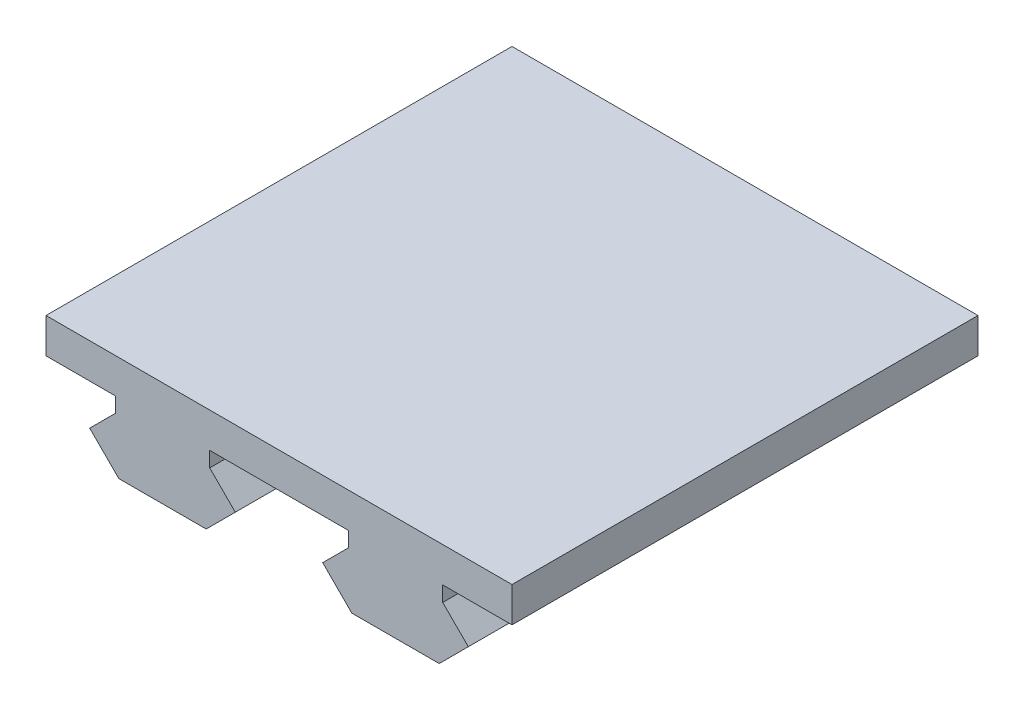
SolidWorks part; units mm, degrees
ref_plane "Front Plane" through (0, 0, 0) normal (0, 0, 1) x (1, 0, 0)
ref_plane "Top Plane" through (0, 0, 0) normal (0, 1, 0) x (1, 0, 0)
ref_plane "Right Plane" through (0, 0, 0) normal (1, 0, 0) x (0, 0, -1)
sketch "Sketch1" plane through (0, 0, 0) normal (0, 1, 0) x (1, 0, 0)
  line L1 (-20, -20) -> (20, -20)
  line L2 (-20, -20) -> (-20, 20)
  line L3 (-20, 20) -> (20, 20)
  line L4 (20, -20) -> (20, 20)
  line L5 (-20, -20) -> (20, 20) construction
  line L6 (-20, 20) -> (20, -20) construction
  point P0 (0, 0)
  dimension "D1" = 40
  dimension "D2" = 40
extrude "Boss-Extrude1" add sketch "Sketch1" along normal blind 3
sketch "Sketch2" plane through (0, 0, 20) normal (0, 0, 1) x (1, 0, 0)
  line L0 (0, 0) -> (-20, 0) construction
  line L1 (-20, 0) -> (20, 0) construction
  line L2 (-10, 0) -> (-10, -6) construction
  line L3 (-13.75, -6) -> (-6.25, -6)
  line L4 (-13.75, -6) -> (-16.25, -3.5)
  line L5 (-16.25, -3.5) -> (-14.0535, -1.3035)
  line L6 (-14.0535, -1.3035) -> (-14.0535, 0)
  line L7 (-14.0535, 0) -> (-5.9465, 0)
  line L8 (-5.9465, -1.3035) -> (-5.9465, 0)
  line L9 (-3.75, -3.5) -> (-5.9465, -1.3035)
  line L10 (-6.25, -6) -> (-3.75, -3.5)
  point P10 (-10, -6)
  dimension "D1" = 7.5
  dimension "D2" = 12.5
  dimension "D3" = 135
  dimension "D4" = 6
  dimension "D5" = 90
extrude "Boss-Extrude2" add sketch "Sketch2" against normal up to surface (40 mm away) up to face at (0, 1.5, -20)
sketch "Sketch3" plane through (0, 0, 0) normal (1, 0, 0) x (0, 0, -1)
  line L0 (20, -6) -> (-20, -6) construction
  line L1 (20, 0) -> (-20, 0) construction
  line L2 (20, -6) -> (-20, -6)
  line L3 (20, 0) -> (-20, 0)
  line L4 (0, -6) -> (0, 0) construction
  line L6 (-6.6667, -6) -> (6.6667, -6)
  line L7 (-6.6667, -6) -> (-6.6667, 0)
  line L8 (-6.6667, 0) -> (6.6667, 0)
  line L9 (6.6667, -6) -> (6.6667, 0)
  line L10 (-6.6667, -6) -> (6.6667, 0) construction
  line L11 (-6.6667, 0) -> (6.6667, -6) construction
  point P7 (0, -3)
  dimension "D1" = 40
  dimension "D2" = 13.3333
extrude "Cut-Extrude1" cut sketch "Sketch3" against normal through all contours L2 L9 L3 L7
mirror "Mirror1" about plane through (0, 0, 0) normal (1, 0, 0) of "Boss-Extrude2", "Cut-Extrude1"
